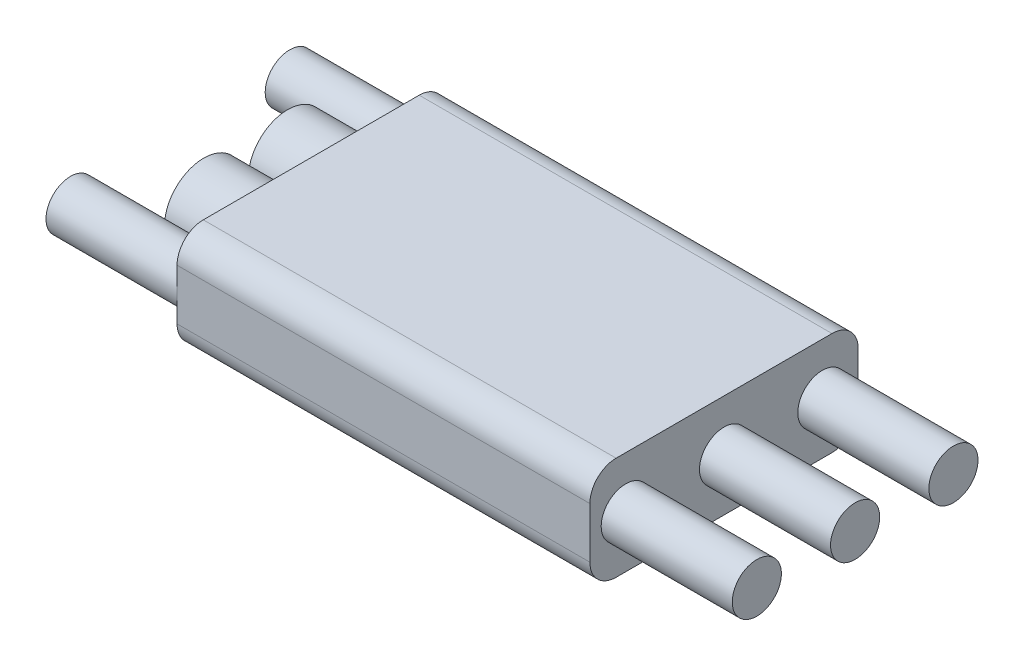
SolidWorks part; units mm, degrees
ref_plane "Front Plane" through (0, 0, 0) normal (0, 0, 1) x (1, 0, 0)
ref_plane "Top Plane" through (0, 0, 0) normal (0, 1, 0) x (1, 0, 0)
ref_plane "Right Plane" through (0, 0, 0) normal (1, 0, 0) x (0, 0, -1)
sketch "Sketch1" plane through (0, 0, 0) normal (0, 1, 0) x (1, 0, 0)
  line L1 (-20, -13) -> (20, -13)
  line L2 (-20, -13) -> (-20, 13)
  line L3 (-20, 13) -> (20, 13)
  line L4 (20, -13) -> (20, 13)
  line L5 (-20, -13) -> (20, 13) construction
  line L6 (-20, 13) -> (20, -13) construction
  point P0 (0, 0)
  dimension "D1" = 40
  dimension "D2" = 26
extrude "ESC Body" add sketch "Sketch1" along normal mid plane 10
sketch "Sketch2" plane through (20, 0, 0) normal (1, 0, 0) x (0, 0, -1)
  circle A0 centre (0, 0) radius 2.3813
  circle A1 centre (-9.525, 0) radius 2.3813
  circle A2 centre (9.525, 0) radius 2.3813
  dimension "D1" = 4.7625
  dimension "D2" = 9.525
  dimension "D3" = 9.525
extrude "Motor Wires" add sketch "Sketch2" along normal blind 12.7
sketch "Sketch3" plane through (-20, 0, 0) normal (-1, 0, 0) x (0, 0, 1)
  circle A0 centre (-4.064, 0) radius 3.81
  circle A1 centre (4.064, 0) radius 3.81
  dimension "D1" = 7.62
  dimension "D2" = 4.064
  dimension "D3" = 4.064
sketch "Sketch4" plane through (-20, 0, 0) normal (-1, 0, 0) x (0, 0, 1)
  line L0 (-13, 5) -> (-13, -5) construction
  line L1 (13, 5) -> (13, -5) construction
  circle A0 centre (-10.6188, 0) radius 2.3813
  circle A1 centre (10.6187, 0) radius 2.3813
  dimension "D1" = 4.7625
  dimension "D2" = 4.7625
extrude "Capacitor Heads" add sketch "Sketch3" along normal blind 6.35
extrude "Power Wires" add sketch "Sketch4" along normal blind 12.7
fillet "Fillet1" radius 2.54 4 edges at (0, -5, 13) (0, -5, -13) (0, 5, -13) (0, 5, 13)
